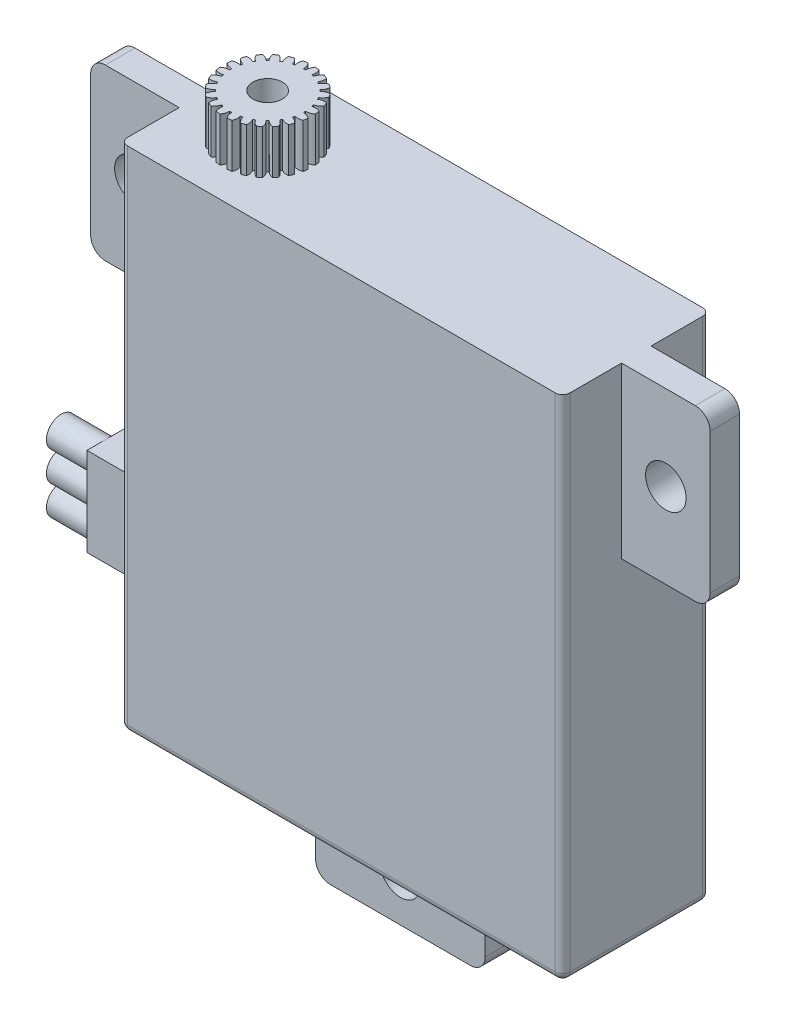
SolidWorks part; units mm, degrees
ref_plane "Front Plane" through (0, 0, 0) normal (0, 0, 1) x (1, 0, 0)
ref_plane "Top Plane" through (0, 0, 0) normal (0, 1, 0) x (1, 0, 0)
ref_plane "Right Plane" through (0, 0, 0) normal (1, 0, 0) x (0, 0, -1)
sketch "Sketch1" plane through (0, 0, 0) normal (0, 0, 1) x (1, 0, 0)
  line L1 (-14.6864, 15.7376) -> (15.3136, 15.7376)
  line L2 (-14.6864, 15.7376) -> (-14.6864, -18.7624)
  line L3 (-14.6864, -18.7624) -> (15.3136, -18.7624)
  line L4 (15.3136, 15.7376) -> (15.3136, -18.7624)
  dimension "D1" = 34.5
  dimension "D2" = 30
extrude "Boss-Extrude1" add sketch "Sketch1" along normal blind 10
ref_plane "Plane1" through (0.3136, 0, 0) normal (1, 0, 0) x (0, 0, -1)
sketch "Sketch2" plane through (0.3136, 0, 0) normal (1, 0, 0) x (0, 0, -1)
  line L0 (-10, -18.7624) -> (0, -18.7624) construction
  line L1 (-10, 15.7376) -> (0, 15.7376)
  line L2 (-10, 15.7376) -> (-10, -18.7624)
  line L3 (-10, -18.7624) -> (0, -18.7624)
  line L4 (0, 15.7376) -> (0, -18.7624)
  line L5 (0, -18.7624) -> (0, 15.7376) construction
  line L6 (-10, -18.7624) -> (-10, 15.7376) construction
  line L7 (-10, -7.2624) -> (0, -7.2624)
  line L8 (-10, 4.2376) -> (0, 4.2376)
  line L9 (-6, 15.7376) -> (-6, 4.2376)
  line L10 (-4, 15.7376) -> (-4, 4.2376)
  dimension "D1" = 34.5
  dimension "D2" = 11.5
  dimension "D3" = 11.5
  dimension "D4" = 2
  dimension "D6" = 4
sketch "Sketch3" plane through (0, -18.7624, 0) normal (0, -1, 0) x (1, 0, 0)
  line L0 (-14.6864, 0) -> (15.3136, 0) construction
  line L1 (-5.4364, 4) -> (6.0636, 4)
  line L2 (-5.4364, 4) -> (-5.4364, 6)
  line L3 (-5.4364, 6) -> (6.0636, 6)
  line L4 (6.0636, 4) -> (6.0636, 6)
  line L5 (-14.6864, 10) -> (-14.6864, 0) construction
  dimension "D1" = 11.5
  dimension "D2" = 2
  dimension "D3" = 4
  dimension "D4" = 9.25
extrude "Boss-Extrude4" add sketch "Sketch2" along normal mid plane 42 contours L10 L1 L9 L8
extrude "Boss-Extrude5" add sketch "Sketch3" along normal blind 6
fillet "Fillet2" radius 1 6 edges at (-5.4364, -24.7624, 5) (6.0636, -24.7624, 5) (21.3136, 4.2376, 5) (21.3136, 15.7376, 5) (-20.6864, 4.2376, 5) (-20.6864, 15.7376, 5)
sketch "Sketch4" plane through (0, 0, 10) normal (0, 0, 1) x (1, 0, 0)
  line L0 (-14.6864, 15.7376) -> (-19.6864, 15.7376) construction
  line L1 (-14.6864, 15.7376) -> (-14.6864, -18.7624) construction
  line L2 (6.0636, -23.7624) -> (6.0636, -18.7624) construction
  line L3 (5.0636, -24.7624) -> (-4.4364, -24.7624) construction
  line L4 (21.3136, 14.7376) -> (21.3136, 5.2376) construction
  line L5 (20.3136, 15.7376) -> (15.3136, 15.7376) construction
  circle A0 centre (-17.6864, 9.9876) radius 1.375
  circle A1 centre (18.3136, 9.9876) radius 1.375
  circle A2 centre (0.3136, -21.7624) radius 1.375
  dimension "D1" = 2.75
  dimension "D4" = 2.75
  dimension "D9" = 2.75
  dimension "D2" = 5.75
  dimension "D3" = 3
  dimension "D5" = 5.75
  dimension "D6" = 3
  dimension "D7" = 3
  dimension "D8" = 5.75
extrude "Cut-Extrude1" cut sketch "Sketch4" against normal blind 10
fillet "Fillet3" radius 0.5 8 edges at (-14.6864, -1.5124, 10) (-14.6864, -1.5124, 0) (-14.6864, -18.7624, 5) (0.3136, -18.7624, 10) (15.3136, -1.5124, 10) (15.3136, -1.5124, 0) (0.3136, -18.7624, 0) (15.3136, -18.7624, 5)
sketch "Sketch5" plane through (-14.6864, 0, 0) normal (-1, 0, 0) x (0, 0, 1)
  line L1 (3.75, -7.2624) -> (6.25, -7.2624)
  line L2 (3.75, -7.2624) -> (3.75, -13.2624)
  line L3 (3.75, -13.2624) -> (6.25, -13.2624)
  line L4 (6.25, -7.2624) -> (6.25, -13.2624)
  line L5 (9.5, -18.7624) -> (0.5, -18.7624) construction
  line L6 (5, 24.0399) -> (5, -41.6909) construction
  line L7 (10, 15.7376) -> (10, -18.2624) construction
  point P4 (5, -7.2624)
  dimension "3 mm" = 2.5
  dimension "D2" = 6
  dimension "D3" = 11.5
  dimension "D4" = 5
extrude "Cut-Extrude2" cut sketch "Sketch5" against normal blind 1
sketch "Sketch6" plane through (0, 15.7376, 0) normal (0, 1, 0) x (1, 0, 0)
  line L0 (-23.0073, -5) -> (30.4309, -5) construction
  line L2 (-20.6864, -6) -> (-20.6864, -4) construction
  line L3 (-14.6864, -4) -> (-14.6864, -0.5) construction
  circle A0 centre (-9.6864, -5) radius 3
  circle A1 centre (-9.6864, -5) radius 1
  point P7 (-20.6864, -5)
  dimension "D2" = 6
  dimension "D3" = 2
  dimension "D1" = 5
extrude "Boss-Extrude6" add sketch "Sketch6" along normal blind 3
sketch "Sketch7" plane through (0, 18.7376, 0) normal (0, 1, 0) x (1, 0, 0)
  line L0 (-9.6864, -5) -> (-9.6864, -0.9081) construction
  line L1 (-9.7614, -2.5) -> (-9.6114, -2.5)
  circle A0 centre (-9.6864, -5) radius 3
  arc A1 (-9.6114, -2.5) -> (-8.8549, -1.7167) centre (-8.8415, -2.4866) cw
  arc A2 (-9.7614, -2.5) -> (-10.5179, -1.7167) centre (-10.5313, -2.4866) ccw
  arc A3 (-9.9268, -2.0096) -> (-9.446, -2.0096) centre (-9.6864, -5) ccw
  point P9 (-9.6864, -2.5)
  circle M4 centre (-9.6864, -5) radius 3
  dimension "D2" = 0.77
  dimension "D1" = 2.5
  dimension "D3" = 0.15
extrude "Cut-Extrude3" cut sketch "Sketch7" against normal blind 3 contours L0 L1 A1 M4 | L1 L0 A0 A2
pattern_circular "CirPattern1" count 24 every 15 about axis through (-9.6864, 0, 5) along (0, 1, 0) of "Cut-Extrude3"
sketch "Sketch8" plane through (-13.6864, 0, 0) normal (-1, 0, 0) x (0, 0, 1)
  line L4 (3.75, -7.2624) -> (3.75, -13.2624)
  line L5 (3.75, -13.2624) -> (6.25, -13.2624)
  line L6 (6.25, -13.2624) -> (6.25, -7.2624)
  line L7 (6.25, -7.2624) -> (3.75, -7.2624)
  line L8 (3.75, -7.2624) -> (3.75, -13.2624)
  line L9 (3.75, -13.2624) -> (6.25, -13.2624)
  line L10 (6.25, -13.2624) -> (6.25, -7.2624)
  line L11 (6.25, -7.2624) -> (3.75, -7.2624)
  dimension "D1" = 0
extrude "Boss-Extrude7" add sketch "Sketch8" along normal blind 7 separate body
sketch "Sketch9" plane through (-20.6864, 0, 0) normal (-1, 0, 0) x (0, 0, 1)
  line L0 (5, -7.2624) -> (5, -9.2624) construction
  line L1 (6.25, -7.2624) -> (3.75, -7.2624) construction
  line L2 (5, -9.2624) -> (5, -11.2624) construction
  line L3 (5, -11.2624) -> (5, -13.2624) construction
  line L4 (3.75, -13.2624) -> (6.25, -13.2624) construction
  circle A0 centre (5, -8.2624) radius 1
  circle A1 centre (5, -10.2624) radius 1
  circle A2 centre (5, -12.2624) radius 1
extrude "Boss-Extrude8" add sketch "Sketch9" along normal blind 3 separate body contours A0 | A1 | A2
